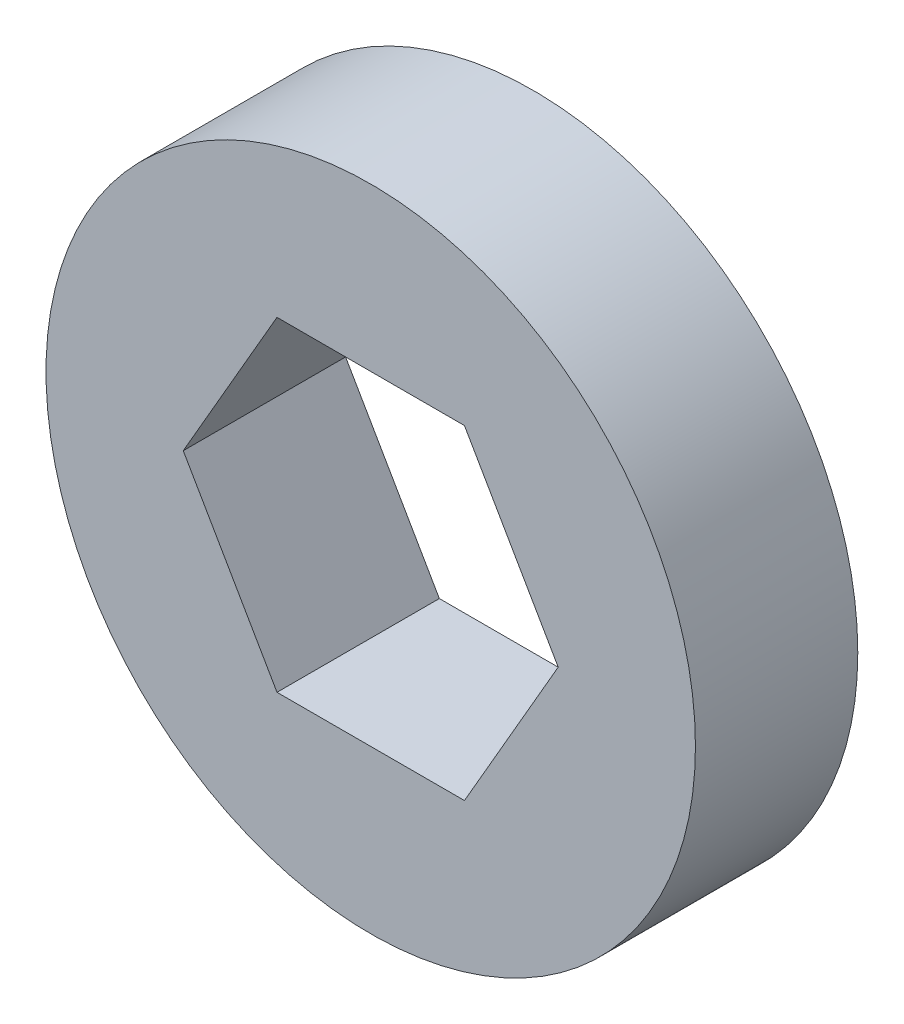
SolidWorks part; units mm, degrees
ref_plane "Front Plane" through (0, 0, 0) normal (0, 0, 1) x (1, 0, 0)
ref_plane "Top Plane" through (0, 0, 0) normal (0, 1, 0) x (1, 0, 0)
ref_plane "Right Plane" through (0, 0, 0) normal (1, 0, 0) x (0, 0, -1)
sketch "Sketch1" plane through (0, 0, 0) normal (0, 0, 1) x (1, 0, 0)
  line L1 (7.3323, 0) -> (3.6662, 6.35)
  line L2 (3.6662, 6.35) -> (-3.6662, 6.35)
  line L3 (-3.6662, 6.35) -> (-7.3323, 0)
  line L4 (-7.3323, 0) -> (-3.6662, -6.35)
  line L5 (-3.6662, -6.35) -> (3.6662, -6.35)
  line L6 (3.6662, -6.35) -> (7.3323, 0)
  circle A0 centre (0, 0) radius 12.7
  circle A1 centre (0, 0) radius 6.35 construction
  dimension "D1" = 12.7
  dimension "D2" = 25.4
extrude "Boss-Extrude1" add sketch "Sketch1" along normal blind 6.35
